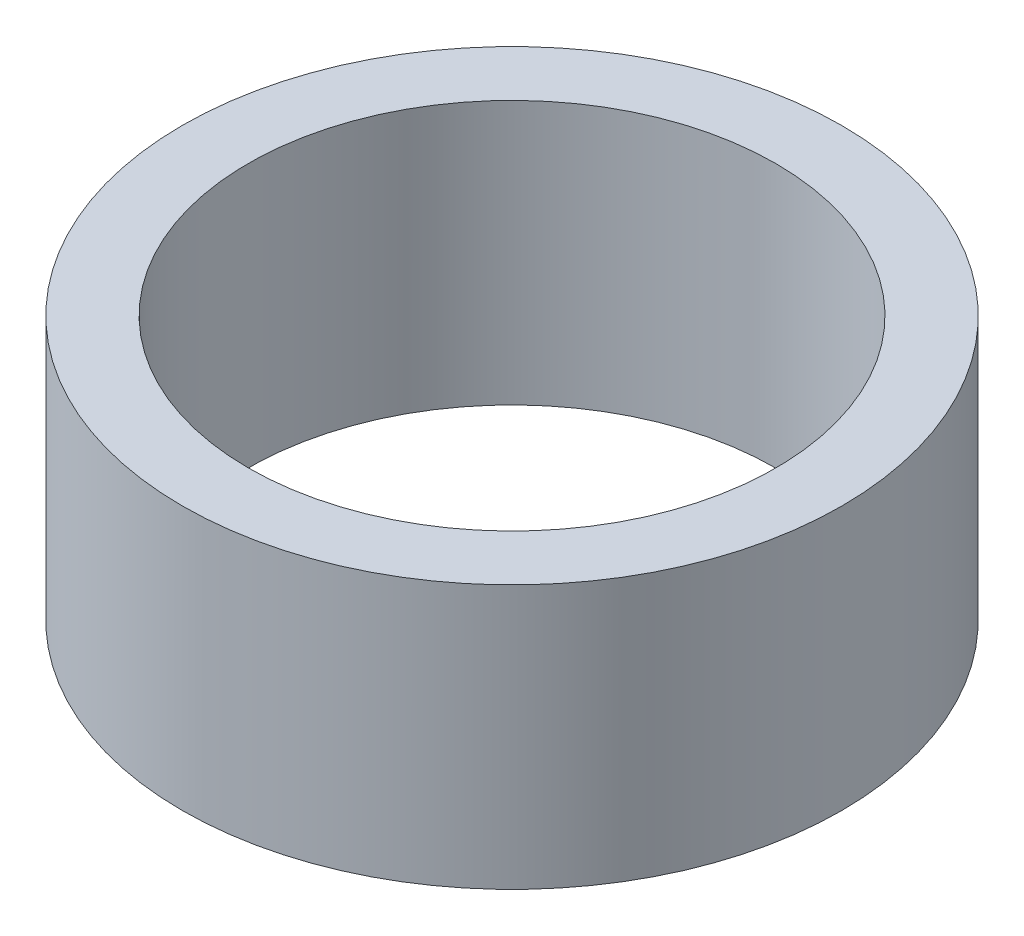
SolidWorks part; units mm, degrees
ref_plane "Plan1" through (0, 0, 0) normal (0, 0, 1) x (1, 0, 0)
ref_plane "Plan2" through (0, 0, 0) normal (0, 1, 0) x (1, 0, 0)
ref_plane "Plan3" through (0, 0, 0) normal (1, 0, 0) x (0, 0, -1)
ref_plane "Plan4" through (0.0788, 608.6802, -0.1198) normal (-0.0001, -1, 0.0002) x (1, -0.0001, 0)
sketch "Esquisse1" plane through (0.0788, 608.6802, -0.1198) normal (-0.0001, -1, 0.0002) x (1, -0.0001, 0)
  circle A0 centre (2143.7061, 669.1106) radius 4
  circle A1 centre (2143.7061, 669.1106) radius 5
  dimension "D1" = 10
  dimension "D2" = 8
extrude "Base-Extrusion" add sketch "Esquisse1" against normal blind 4
